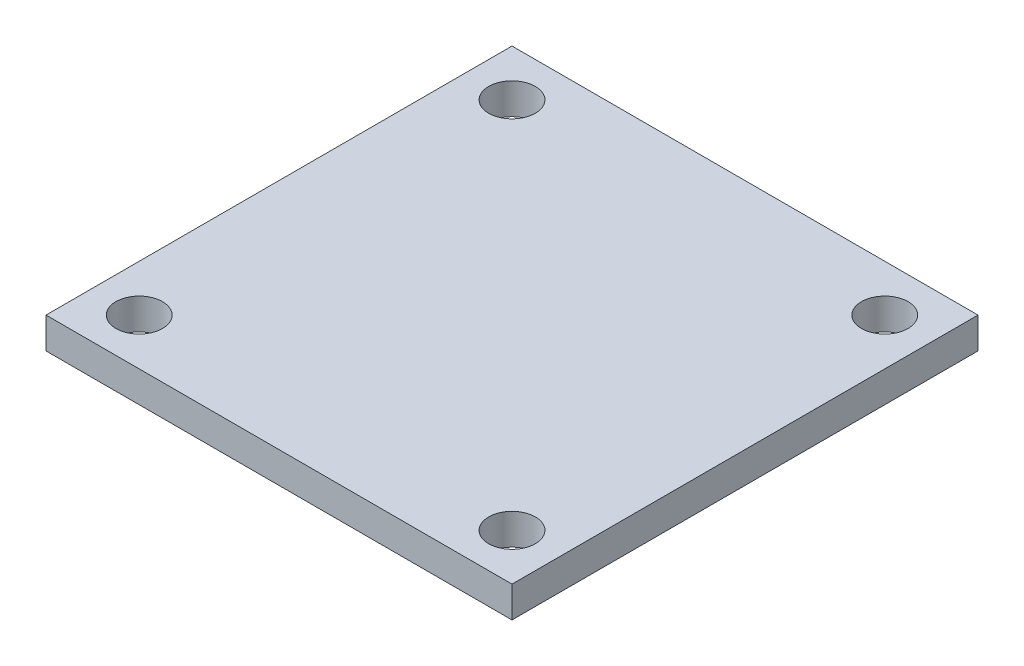
SolidWorks part; units mm, degrees
ref_plane "Front Plane" through (0, 0, 0) normal (0, 0, 1) x (1, 0, 0)
ref_plane "Top Plane" through (0, 0, 0) normal (0, 1, 0) x (1, 0, 0)
ref_plane "Right Plane" through (0, 0, 0) normal (1, 0, 0) x (0, 0, -1)
sketch "Sketch1" plane through (0, 0, 0) normal (0, 1, 0) x (1, 0, 0)
  line L0 (0, 15) -> (0, -15) construction
  line L1 (-15, -15) -> (15, -15)
  line L2 (-15, -15) -> (-15, 15)
  line L3 (-15, 15) -> (15, 15)
  line L4 (15, -15) -> (15, 15)
  line L5 (-15, -15) -> (15, 15) construction
  line L6 (-15, 15) -> (15, -15) construction
  line L7 (-15, 0) -> (15, 0) construction
  circle A0 centre (-12, 12) radius 1.5
  circle A1 centre (12, 12) radius 1.5
  circle A2 centre (12, -12) radius 1.5
  circle A3 centre (-12, -12) radius 1.5
  point P0 (0, 0)
  dimension "D2" = 3
  dimension "D1" = 30
  dimension "D3" = 3
extrude "Boss-Extrude1" add sketch "Sketch1" along normal blind 2
